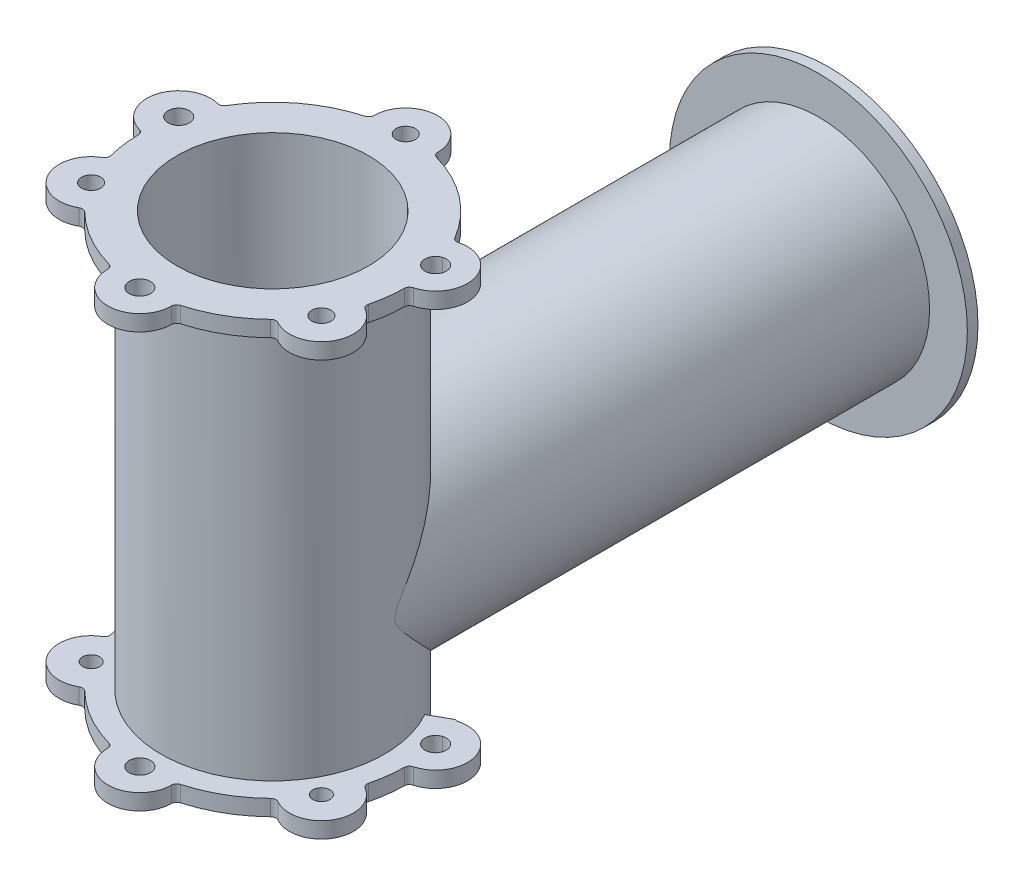
SolidWorks part; units mm, degrees
material "6061-T6 (SS)"
ref_plane "Front" through (0, 0, 0) normal (0, 0, 1) x (1, 0, 0)
ref_plane "Top" through (0, 0, 0) normal (0, 1, 0) x (1, 0, 0)
ref_plane "Right" through (0, 0, 0) normal (1, 0, 0) x (0, 0, -1)
sketch "Sketch1" plane through (0, 0, 0) normal (0, 1, 0) x (1, 0, 0)
  circle A0 centre (0, 0) radius 9
  circle A1 centre (0, 0) radius 10.5
  dimension "D1" = 18
  dimension "D2" = 21
extrude "Boss-Extrude1" add sketch "Sketch1" along normal blind 37.5
sketch "Sketch2" plane through (0, 37.5, 0) normal (0, 1, 0) x (1, 0, 0)
  line L0 (0, 10.5) -> (0, 12.5) construction
  line L1 (0, 0) -> (0, -12.5) construction
  line L2 (3, 0) -> (3, -12.5)
  line L3 (-3, 0) -> (-3, -12.5)
  line L4 (0, 0) -> (0, 12.5) construction
  line L7 (-3, 0) -> (-3, 12.5)
  line L10 (3, 0) -> (3, 12.5)
  line L11 (-1.5, -2.5981) -> (9.3253, -8.8481)
  line L12 (1.5, 2.5981) -> (12.3253, -3.6519)
  line L13 (0, 0) -> (10.8253, -6.25) construction
  line L14 (-1.5, 2.5981) -> (-12.3253, -3.6519)
  line L15 (1.5, -2.5981) -> (-9.3253, -8.8481)
  line L16 (0, 0) -> (-10.8253, -6.25) construction
  line L17 (0, 0) -> (-12.0741, 3.2352) construction
  line L18 (-0.7765, -2.8978) -> (-12.8505, 0.3375)
  line L19 (0.7765, 2.8978) -> (-11.2976, 6.133)
  line L20 (0, 36.7398) -> (0, -36.7398) construction
  line L21 (0, 0) -> (12.0741, 3.2352) construction
  line L22 (0.7765, -2.8978) -> (12.8505, 0.3375)
  line L23 (-0.7765, 2.8978) -> (11.2976, 6.133)
  circle A0 centre (0, 0) radius 9 construction
  circle A1 centre (0, 0) radius 9
  circle A2 centre (0, 0) radius 12.5
  circle A3 centre (0, 0) radius 10.5 construction
  arc A4 (3, 0) -> (-3, 0) centre (0, 0) ccw
  arc A5 (-3, -12.5) -> (3, -12.5) centre (0, -12.5) ccw
  circle A16 centre (0, -12.5) radius 1
  arc A22 (-3, 0) -> (3, 0) centre (0, 0) ccw
  arc A23 (3, 12.5) -> (-3, 12.5) centre (0, 12.5) ccw
  arc A25 (1.5, 2.5981) -> (-1.5, -2.5981) centre (0, 0) ccw
  arc A26 (9.3253, -8.8481) -> (12.3253, -3.6519) centre (10.8253, -6.25) ccw
  arc A28 (1.5, -2.5981) -> (-1.5, 2.5981) centre (0, 0) ccw
  arc A29 (-12.3253, -3.6519) -> (-9.3253, -8.8481) centre (-10.8253, -6.25) ccw
  arc A31 (-0.7765, -2.8978) -> (0.7765, 2.8978) centre (0, 0) ccw
  arc A32 (-11.2976, 6.133) -> (-12.8505, 0.3375) centre (-12.0741, 3.2352) ccw
  arc A33 (0.7765, -2.8978) -> (-0.7765, 2.8978) centre (0, 0) cw
  arc A34 (11.2976, 6.133) -> (12.8505, 0.3375) centre (12.0741, 3.2352) cw
  circle A35 centre (-12.0741, 3.2352) radius 1
  circle A36 centre (12.0741, 3.2352) radius 1
  point P8 (0, 11.5)
  point P10 (0, -6.25)
  point P19 (0, 6.25)
  point P29 (-6.037, 1.6176)
  point P31 (5.4127, -3.125)
  point P39 (-5.4127, -3.125)
  point P52 (6.037, 1.6176)
  point P55 (0, 0)
  dimension "D1" = 25
  dimension "D3" = 3
  dimension "D5" = 2
  dimension "D7" = 75
  dimension "D2" = 12.5
  dimension "D6" = 3
extrude "Boss-Extrude2" add sketch "Sketch2" along normal blind 1.5
ref_plane "Plane1" through (0, 18.75, 0) normal (0, -1, 0) x (-1, 0, 0)
fillet "Fillet1" radius 0.5 12 edges at (-3, 38.25, 12.1347) (3, 38.25, 12.1347) (9.0089, 38.25, 8.6654) (12.0089, 38.25, 3.4693) (12.4976, 38.25, -0.2429) (10.9447, 38.25, -6.0385) (3, 38.25, -12.1347) (-3, 38.25, -12.1347) (-10.9447, 38.25, -6.0385) (-12.4976, 38.25, -0.2429) (-12.0089, 38.25, 3.4693) (-9.0089, 38.25, 8.6654)
mirror "Mirror1" about plane through (0, 18.75, 0) normal (0, -1, 0) of "Boss-Extrude2", "Fillet1"
sketch "Sketch10" plane through (0, 0, 0) normal (0, 0, 1) x (1, 0, 0)
  line L0 (0, 0) -> (0, 10.55) construction
  circle A0 centre (0, 10.55) radius 7.65
  dimension "D2" = 15.3
  dimension "D1" = 10.55
extrude "Cut-Extrude1" cut sketch "Sketch10" against normal through all
sketch "Sketch11" plane through (0, -1.5, 0) normal (0, -1, 0) x (1, 0, 0)
  line L0 (0, 0) -> (0, -12.5) construction
  line L1 (0, 0) -> (-10.8253, 6.25) construction
  line L2 (0, 0) -> (10.8253, 6.25) construction
  dimension "D2" = 12.5
  dimension "D1" = 3
sketch "Sketch13" plane through (0, 39, 0) normal (0, 1, 0) x (1, 0, 0)
  line L0 (0, 0) -> (10.8253, -6.25) construction
  line L1 (0, 0) -> (-10.8253, -6.25) construction
  line L2 (0, 0) -> (0, 12.5) construction
  line L3 (0, 0) -> (10.8253, -6.25)
  line L4 (0, 0) -> (-10.8253, -6.25)
  line L5 (0, 0) -> (0, 12.5)
  circle A0 centre (0, 12.5) radius 0.9
  circle A1 centre (-10.8253, -6.25) radius 0.9
  circle A2 centre (10.8253, -6.25) radius 0.9
  dimension "D1" = 1.8
extrude "Cut-Extrude2" cut sketch "Sketch13" against normal up to surface (1.5 mm away) up to face at (0, 37.5, 10.5)
hole_wizard "M2x0.4 Tapped Hole3" positions "3DSketch2" profile "Sketch14" tap size "M2x0.4" standard "ANSI Metric"
sketch3d "3DSketch2"
  point P0 (10.8253, -1.5, 6.25)
  point P3 (0, -1.5, -12.5)
  point P6 (-10.8253, -1.5, 6.25)
sketch "Sketch14" plane through (10.8253, -1.5, 6.25) normal (1, 0, 0) x (0, 0, -1)
  line L0 (0, 0) -> (0, 1.9797)
  line L1 (0, 1.9797) -> (0.8, 1.499)
  line L2 (0.8, 1.499) -> (0.8, 0)
  line L5 (0.8, 0) -> (0, 0)
  line L10 (0, 1.9797) -> (-0.8, 1.499) construction
  line L11 (0, -6.35) -> (0, 107.95) construction
  dimension "Tap Drill Dia." = 1.6
  dimension "Tap Drill Depth" = 1.499
  dimension "Drill Angle" = 118
cosmetic thread "Hole Thread1" parameters "D1"=1.5, "D2"=2
cosmetic thread "Hole Thread2" parameters "D1"=1.5, "D2"=2
cosmetic thread "Hole Thread3" parameters "D1"=1.5, "D2"=2
sketch "Sketch18" plane through (0, -1.5, 0) normal (0, -1, 0) x (1, 0, 0)
  line L0 (0, 0) -> (-10.9974, -6.1587)
  line L1 (0, 0) -> (10.9974, -6.1587)
  arc A2 (-10.7572, -6.3664) -> (-11.3142, -6.1374) centre (-11.1875, -6.6211) ccw construction
  arc A3 (11.3142, -6.1374) -> (10.7572, -6.3664) centre (11.1875, -6.6211) ccw construction
  arc A5 (-10.9974, -6.1587) -> (10.9974, -6.1587) centre (0, -4.3558) ccw
  circle A6 centre (0, 0) radius 10.5 construction
  circle A7 centre (0, 0) radius 10.5
  arc A8 (-3, -12.5171) -> (3, -12.5171) centre (0, -12.5) ccw construction
  point P1 (0, 0)
  point P2 (0, -15.5)
  point P17 (0, -15.5)
  circle M7 centre (0, -12.5) radius 0.8
  arc M22 (-11.3142, -6.1374) -> (-10.7572, -6.3664) centre (-11.1875, -6.6211) cw
  arc M23 (-10.7572, -6.3664) -> (-3.3653, -12.0385) centre (0, 0) ccw
  arc M24 (-3.3653, -12.0385) -> (-3, -12.5171) centre (-3.4999, -12.52) cw
  arc M25 (-3, -12.5171) -> (3, -12.5171) centre (0, -12.5) ccw
  arc M26 (3, -12.5171) -> (3.3653, -12.0385) centre (3.4999, -12.52) cw
  arc M27 (3.3653, -12.0385) -> (10.7572, -6.3664) centre (0, 0) ccw
  arc M28 (10.7572, -6.3664) -> (11.3142, -6.1374) centre (11.1875, -6.6211) cw
extrude "Cut-Extrude4" cut sketch "Sketch18" against normal blind 1.5 contours A7 L0 L1 M22 M23 M24 M25 M26 M27 M28 M7
sketch "Sketch15" plane through (0, 0, 0) normal (0, 0, 1) x (1, 0, 0)
  circle A0 centre (0, 10.55) radius 7.65 construction
  circle A1 centre (0, 10.55) radius 7.65 construction
  circle A2 centre (0, 10.55) radius 9.55
  circle A3 centre (0, 10.55) radius 10.45
  dimension "D1" = 19.1
  dimension "D2" = 0.9
extrude "Boss-Extrude3" add sketch "Sketch15" against normal blind 51.3
sketch "Sketch16" plane through (0, 39, 0) normal (0, 1, 0) x (1, 0, 0)
  circle A0 centre (0, 0) radius 9 construction
  circle A1 centre (0, 0) radius 9
extrude "Cut-Extrude3" cut sketch "Sketch16" against normal through all
sketch "Sketch17" plane through (0, 0, -51.3) normal (0, 0, -1) x (-1, 0, 0)
  circle A0 centre (0, 10.55) radius 9.55 construction
  circle A1 centre (0, 10.55) radius 9.55
  circle A2 centre (0, 10.55) radius 14
  dimension "D1" = 28
extrude "Boss-Extrude4" add sketch "Sketch17" along normal blind 1
